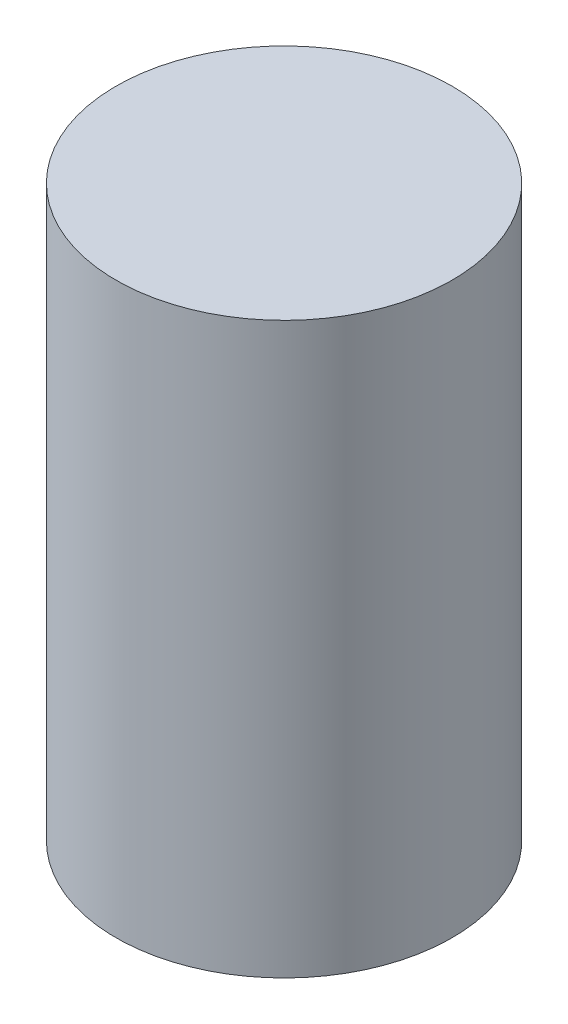
SolidWorks part; units mm, degrees
ref_plane "Front" through (0, 0, 0) normal (0, 0, 1) x (1, 0, 0)
ref_plane "Top" through (0, 0, 0) normal (0, 1, 0) x (1, 0, 0)
ref_plane "Right" through (0, 0, 0) normal (1, 0, 0) x (0, 0, -1)
sketch "Эскиз1" plane through (0, 0, 0) normal (0, 1, 0) x (1, 0, 0)
  circle A0 centre (0, 0) radius 540
  dimension "D1" = 1080
extrude "Бобышка-Вытянуть1" add sketch "Эскиз1" along normal blind 1830
sketch "Эскиз4" plane through (0, 0, 0) normal (0, -1, 0) x (1, 0, 0)
  circle A0 centre (0, 0) radius 21.15
  dimension "D1" = 42.3
extrude "Бобышка-Вытянуть4" add sketch "Эскиз4" along normal blind 30
